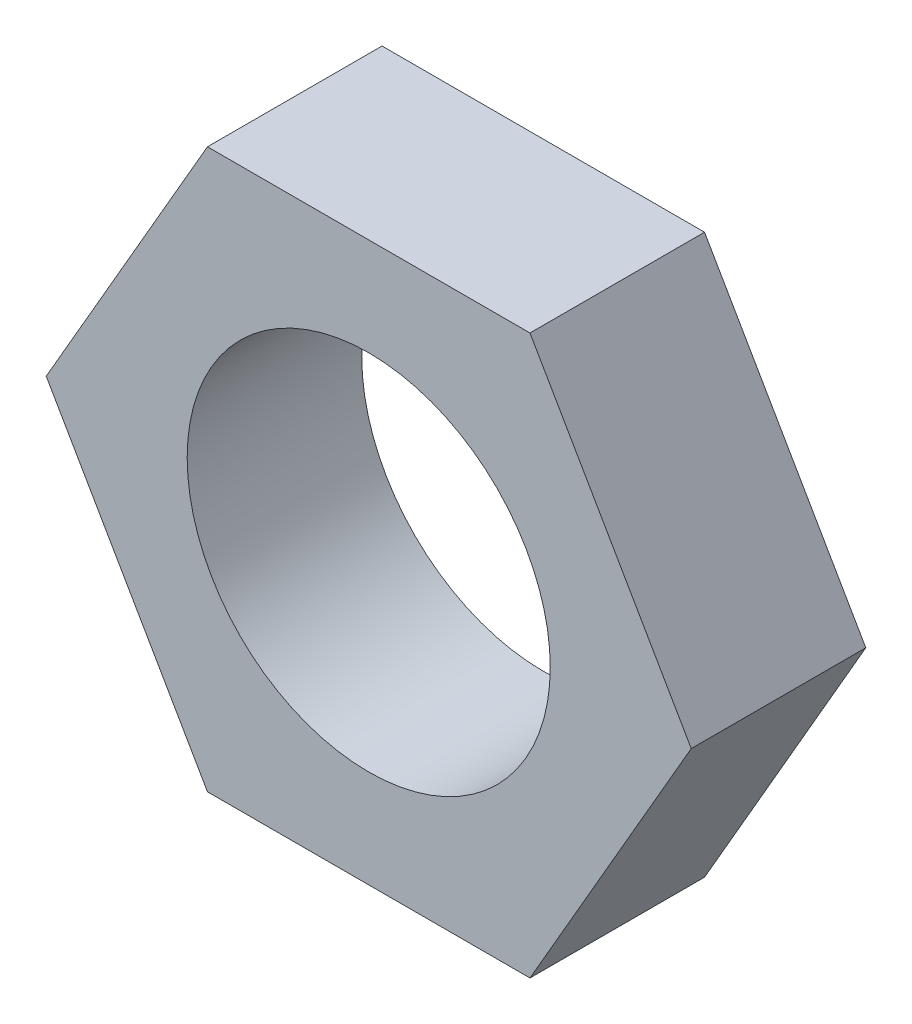
SolidWorks part; units mm, degrees
ref_plane "前视基准面" through (0, 0, 0) normal (0, 0, 1) x (1, 0, 0)
ref_plane "上视基准面" through (0, 0, 0) normal (0, 1, 0) x (1, 0, 0)
ref_plane "右视基准面" through (0, 0, 0) normal (1, 0, 0) x (0, 0, -1)
other "Configuration Table"
sketch "草图1" plane through (0, 0, 0) normal (0, 0, 1) x (1, 0, 0)
  line L0 (4.6188, 0) -> (2.3094, 4)
  line L1 (2.3094, 4) -> (-2.3094, 4)
  line L2 (-2.3094, 4) -> (-4.6188, 0)
  line L3 (-4.6188, 0) -> (-2.3094, -4)
  line L4 (-2.3094, -4) -> (2.3094, -4)
  line L5 (2.3094, -4) -> (4.6188, 0)
  circle A0 centre (0, 0) radius 2.6
extrude "M5薄螺母外形占位" add sketch "草图1" along normal blind 2.5
